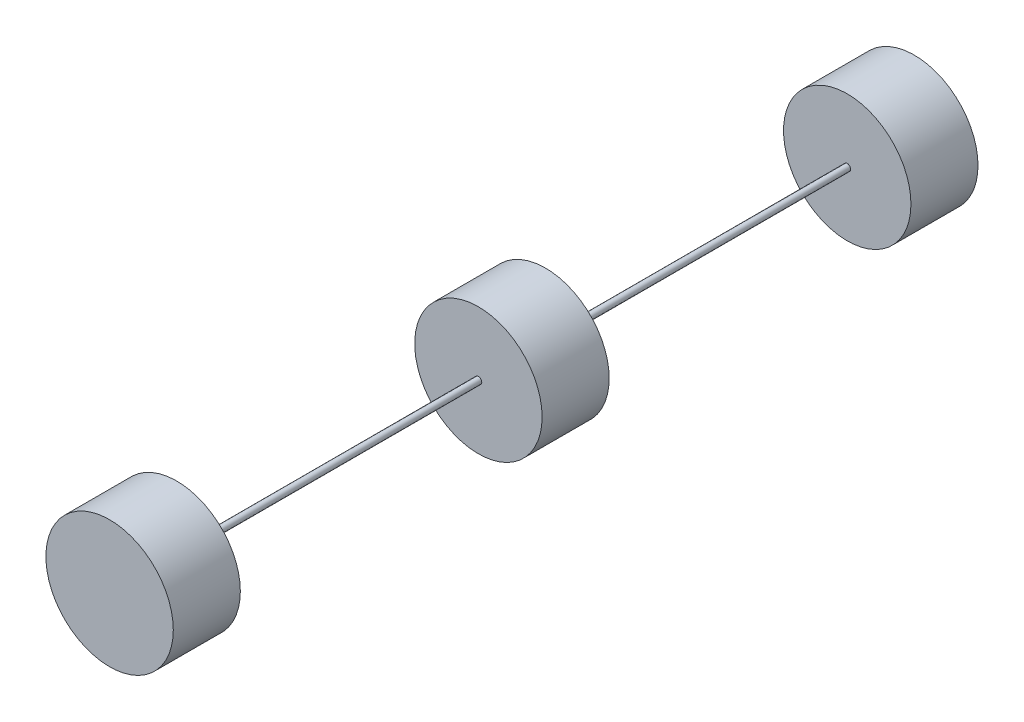
SolidWorks part; units mm, degrees
ref_plane "前视基准面" through (0, 0, 0) normal (0, 0, 1) x (1, 0, 0)
ref_plane "上视基准面" through (0, 0, 0) normal (0, 1, 0) x (1, 0, 0)
ref_plane "右视基准面" through (0, 0, 0) normal (1, 0, 0) x (0, 0, -1)
sketch "草图1" plane through (0, 0, 0) normal (0, 0, 1) x (1, 0, 0)
  circle A0 centre (0, 0) radius 19
extrude "凸台-拉伸1" add sketch "草图1" along normal blind 20
sketch "草图2" plane through (0, 0, 20) normal (0, 0, 1) x (1, 0, 0)
  circle A0 centre (0, 0) radius 1
extrude "凸台-拉伸2" add sketch "草图2" along normal blind 90
sketch "草图3" plane through (0, 0, 110) normal (0, 0, 1) x (1, 0, 0)
  circle A0 centre (0, 0) radius 19
extrude "凸台-拉伸3" add sketch "草图3" along normal blind 20
sketch "草图4" plane through (0, 0, 130) normal (0, 0, 1) x (1, 0, 0)
  circle A0 centre (0, 0) radius 1
extrude "凸台-拉伸4" add sketch "草图4" along normal blind 90
sketch "草图5" plane through (0, 0, 220) normal (0, 0, 1) x (1, 0, 0)
  circle A0 centre (0, 0) radius 19
extrude "凸台-拉伸5" add sketch "草图5" along normal blind 20
